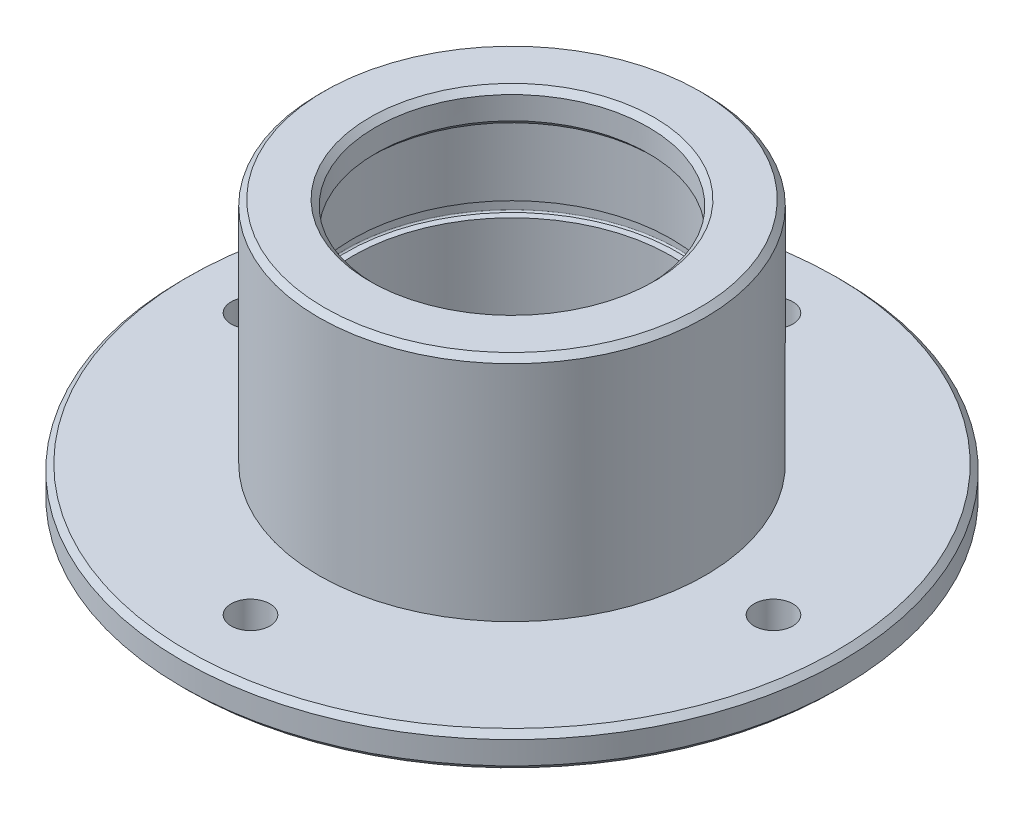
SolidWorks part; units mm, degrees
ref_plane "Front" through (0, 0, 0) normal (0, 0, 1) x (1, 0, 0)
ref_plane "Top" through (0, 0, 0) normal (0, 1, 0) x (1, 0, 0)
ref_plane "Right" through (0, 0, 0) normal (1, 0, 0) x (0, 0, -1)
sketch "Sketch1" plane through (0, 0, 0) normal (0, 0, 1) x (1, 0, 0)
  line L0 (0, 17.954) -> (0, -17.7415) construction
  line L2 (14, -3) -> (14, 17.15)
  line L4 (17, 20.15) -> (17, 0)
  line L5 (17, 0) -> (29, 0)
  line L6 (29, 0) -> (29, -3)
  line L7 (29, -3) -> (14, -3)
  line L9 (17, 20.15) -> (12, 20.15)
  line L10 (12, 20.15) -> (12, 17.15)
  line L11 (12, 17.15) -> (14, 17.15)
  line L12 (-12.05, 10.15) -> (12.05, 10.15) construction
  dimension "D1" = 3
  dimension "D2" = 14
  dimension "D3" = 12
  dimension "D4" = 12
  dimension "D5" = 3
  dimension "D6" = 3
  dimension "D7" = 7
revolve "Revolve1" add sketch "Sketch1" angle 360 about L0
sketch "Sketch2" [suppressed] plane through (0, 0, 0) normal (0, 1, 0) x (1, 0, 0)
  circle A0 centre (0, 0) radius 11
extrude "Cut-Extrude1" [suppressed] cut sketch "Sketch2" against normal through all
ref_plane "Plane1" through (0, 17.954, 0) normal (-1, 0, 0) x (0, 0, 1)
hole_wizard "M3 Clearance Hole1" positions "Sketch5" profile "Sketch6" hole size "M3" standard "ISO" end condition through all
sketch "Sketch5" plane through (0, 0, 0) normal (0, 1, 0) x (1, 0, 0)
  circle A0 centre (0, 0) radius 23 construction
  point P0 (0, 23)
  point P7 (23, 0)
  point P9 (0, -23)
  point P11 (-23, 0)
  dimension "D1" = 46
sketch "Sketch6" plane through (0, 0, -23) normal (1, 0, 0) x (0, 0, 1)
  line L0 (0, 0) -> (0, 3)
  line L1 (0, 3) -> (1.7, 3)
  line L2 (1.7, 3) -> (1.7, 0)
  line L5 (1.7, 0) -> (0, 0)
  line L11 (0, -6.35) -> (0, 107.95) construction
  dimension "Thru Hole Dia." = 3.4
  dimension "Thru Hole Depth" = 3
fillet "Fillet1" radius 0.2 1 edges at (0, 17.15, 14)
chamfer "Chamfer1" distance 0.5 angle 45 6 edges at (0, -3, 14) (0, 20.15, 17) (0, 20.15, 12) (0, 17.15, 12) (0, -3, 29) (0, 0, 29)
ref_plane "Plane2" through (0, 17.954, 0) normal (-1, 0, 0) x (0, 0, 1)
sketch "Sketch8" plane through (0, 17.954, 0) normal (-1, 0, 0) x (0, 0, 1)
  line L0 (14.57, -9.104) -> (12.6, -9.104)
  line L1 (12.6, -9.104) -> (12.6, -7.804)
  line L2 (12.6, -7.804) -> (14.57, -7.804)
  line L3 (14.7, -7.934) -> (14.7, -8.974)
  line L4 (0, -50) -> (0, 50) construction
  line L5 (-12.5, -0.804) -> (12.5, -0.804) construction
  arc A0 (14.7, -8.974) -> (14.57, -9.104) centre (14.57, -8.974) cw
  arc A1 (14.7, -7.934) -> (14.57, -7.804) centre (14.57, -7.934) ccw
  dimension "D1" = 0.13
  dimension "D2" = 0.13
  dimension "D3" = 7
revolve "Groove for BS 3673 P4 - B028M, Internal Circlip1" cut sketch "Sketch8"
